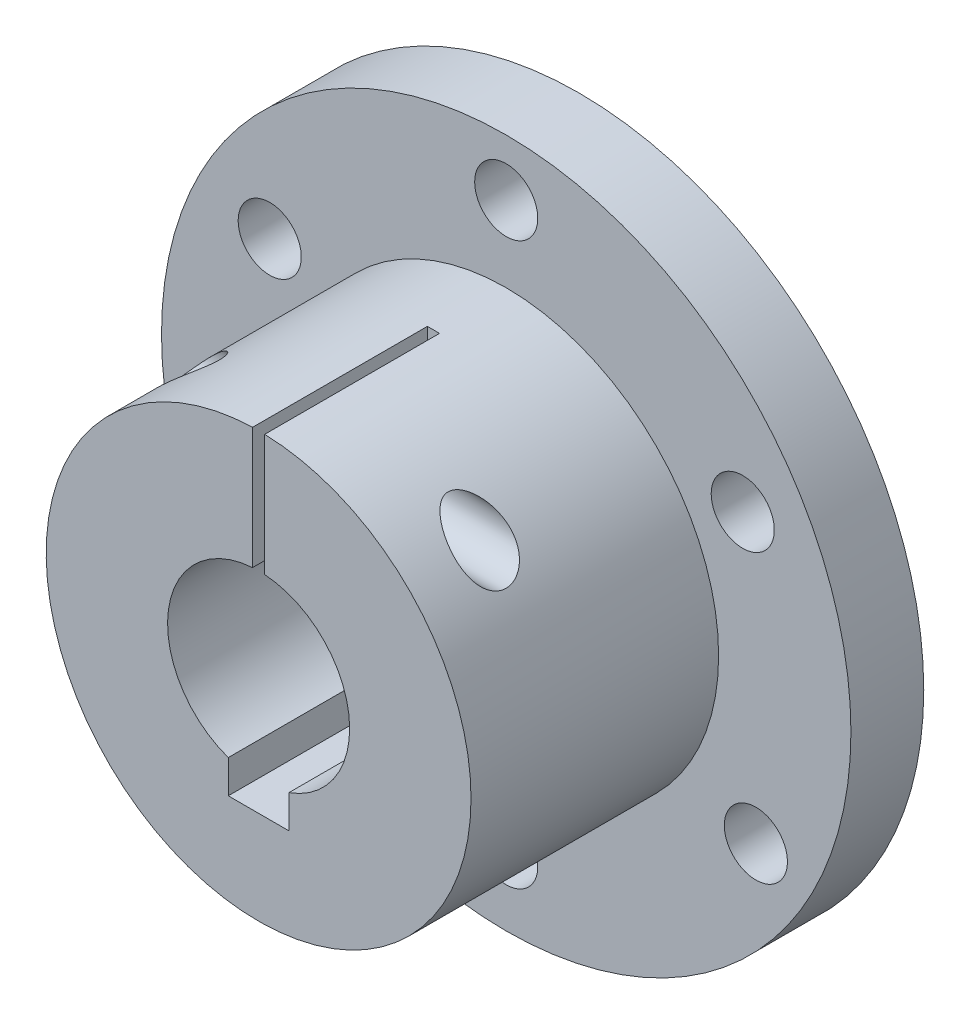
SolidWorks part; units mm, degrees
ref_plane "前视基准面" through (0, 0, 0) normal (0, 0, 1) x (1, 0, 0)
ref_plane "上视基准面" through (0, 0, 0) normal (0, 1, 0) x (1, 0, 0)
ref_plane "右视基准面" through (0, 0, 0) normal (1, 0, 0) x (0, 0, -1)
other "Configuration Table"
sketch "草图1" plane through (0, 0, 0) normal (1, 0, 0) x (0, 0, -1)
  line L0 (-31.4, 0) -> (5, 0) construction
  line L1 (0, 7.5) -> (0, 28.4)
  line L2 (0, 28.4) -> (-6, 28.4)
  line L3 (-6, 28.4) -> (-6, 17.5)
  line L4 (-6, 17.5) -> (-26.4, 17.5)
  line L5 (-26.4, 17.5) -> (-26.4, 7.5)
  line L6 (-26.4, 7.5) -> (0, 7.5)
revolve "旋转1" add sketch "草图1" angle 360 about L0
sketch "草图2" plane through (0, 0, 0) normal (0, 0, 1) x (1, 0, 0)
  circle A0 centre (0, 23.75) radius 2.6
  circle A1 centre (-20.5681, -11.875) radius 2.6
  circle A2 centre (20.5681, -11.875) radius 2.6
  circle A3 centre (19.4856, 11.25) radius 2.6
  circle A4 centre (-19.4856, 11.25) radius 2.6
  circle A5 centre (0, -22.5) radius 2.6
extrude "切除-拉伸1" cut sketch "草图2" along normal through all
sketch "草图3" plane through (0, 0, 0) normal (0, 0, 1) x (1, 0, 0)
  line L1 (-2.5, -9.8) -> (2.5, -9.8)
  line L2 (-2.5, -9.8) -> (-2.5, -6.5)
  line L3 (-2.5, -6.5) -> (2.5, -6.5)
  line L4 (2.5, -9.8) -> (2.5, -6.5)
extrude "切除-拉伸2" cut sketch "草图3" along normal through all
sketch "草图4" plane through (0, 0, 0) normal (0, 0, 1) x (1, 0, 0)
  line L1 (-0.5, 7) -> (0.5, 7)
  line L2 (-0.5, 7) -> (-0.5, 18)
  line L3 (-0.5, 18) -> (0.5, 18)
  line L4 (0.5, 7) -> (0.5, 18)
extrude "切除-拉伸3" cut sketch "草图4" along normal blind 14.4 from offset 12
sketch "草图5" plane through (0, 0, 0) normal (1, 0, 0) x (0, 0, -1)
  circle A0 centre (-20.2, 12.5) radius 2.25
extrude "切除-拉伸4" cut sketch "草图5" against normal through all and the other way through all
